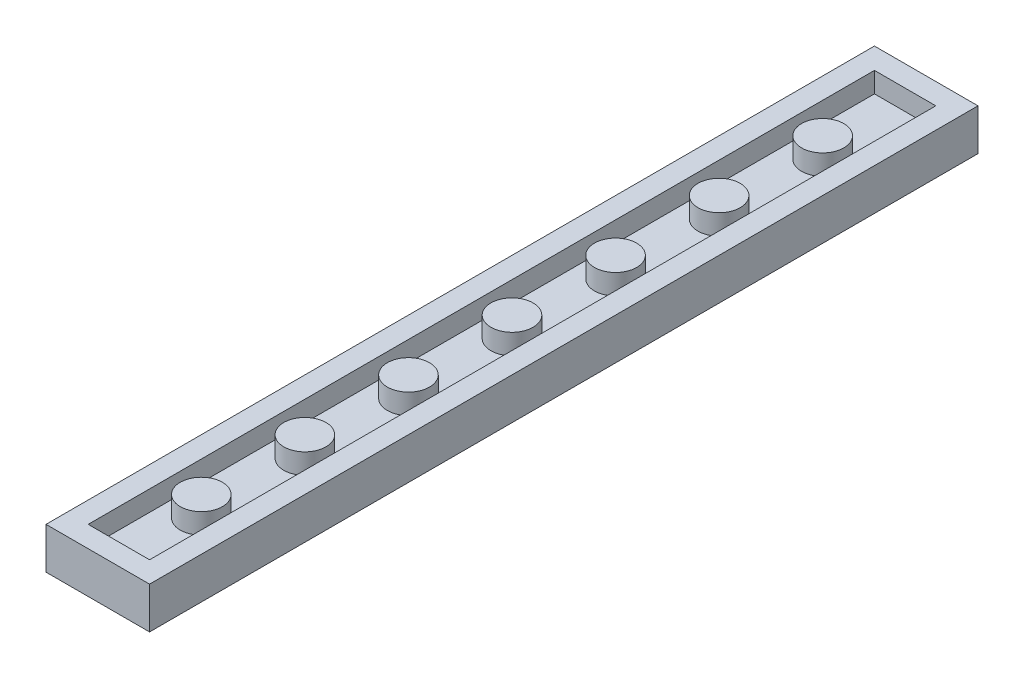
SolidWorks part; units mm, degrees
ref_plane "Front Plane" through (0, 0, 0) normal (0, 0, 1) x (1, 0, 0)
ref_plane "Top Plane" through (0, 0, 0) normal (0, 1, 0) x (1, 0, 0)
ref_plane "Right Plane" through (0, 0, 0) normal (1, 0, 0) x (0, 0, -1)
ref_plane "Plane1" through (0, 3.226, 0) normal (0, 1, 0) x (1, 0, 0)
sketch "Sketch1" plane through (0, 3.226, 0) normal (0, 1, 0) x (1, 0, 0)
  line L0 (4.0325, -16.13) -> (4.0325, 48.39)
  line L1 (4.0325, 48.39) -> (-4.0325, 48.39)
  line L2 (-4.0325, 48.39) -> (-4.0325, -16.13)
  line L3 (-4.0325, -16.13) -> (4.0325, -16.13)
  dimension "D1" = 64.52
extrude "Boss-Extrude1" add sketch "Sketch1" against normal blind 3.226
sketch "Sketch2" plane through (0, 3.226, 0) normal (0, 1, 0) x (-1, 0, 0)
  line L0 (2.39, 14.4875) -> (-2.39, 14.4875)
  line L1 (-2.39, 14.4875) -> (-2.39, -14.4875)
  line L3 (2.39, -14.4875) -> (2.39, 14.4875)
  line L6 (2.39, -46.7475) -> (-2.39, -46.7475)
  line L7 (-2.39, -46.7475) -> (-2.39, -14.4875)
  line L8 (2.39, -14.4875) -> (2.39, -46.7475)
extrude "Cut-Extrude1" cut sketch "Sketch2" against normal blind 1.5835
ref_plane "Plane2" through (0, 0, 12.0975) normal (0, 0, -1) x (-1, 0, 0)
ref_plane "Plane3" through (0, 0, 4.0325) normal (0, 0, -1) x (-1, 0, 0)
ref_plane "Plane4" through (0, 0, -4.0325) normal (0, 0, -1) x (-1, 0, 0)
ref_plane "Plane5" through (0, 0, -12.0975) normal (0, 0, -1) x (-1, 0, 0)
ref_plane "Plane6" through (0, 0, -8.065) normal (0, 0, -1) x (-1, 0, 0)
sketch "Sketch7" plane through (0, 0, -8.065) normal (0, 0, -1) x (-1, 0, 0)
  line L0 (-1.6425, 1.6425) -> (0, 1.6425)
  line L1 (0, 1.6425) -> (0, 3.226)
  line L2 (0, 3.226) -> (-1.6425, 3.226)
  line L3 (-1.6425, 3.226) -> (-1.6425, 1.6425)
  line L4 (0, 1.6425) -> (0, 3.226) construction
revolve "Revolve5" add sketch "Sketch7" angle 360 about L4
ref_plane "Plane7" through (0, 0, 0) normal (0, 0, -1) x (-1, 0, 0)
sketch "Sketch8" plane through (0, 0, 0) normal (0, 0, -1) x (-1, 0, 0)
  line L0 (-1.6425, 1.6425) -> (0, 1.6425)
  line L1 (0, 1.6425) -> (0, 3.226)
  line L2 (0, 3.226) -> (-1.6425, 3.226)
  line L3 (-1.6425, 3.226) -> (-1.6425, 1.6425)
  line L4 (0, 1.6425) -> (0, 3.226) construction
revolve "Revolve6" add sketch "Sketch8" angle 360 about L4
ref_plane "Plane8" through (0, 0, 8.065) normal (0, 0, -1) x (-1, 0, 0)
sketch "Sketch9" plane through (0, 0, 8.065) normal (0, 0, -1) x (-1, 0, 0)
  line L0 (-1.6425, 1.6425) -> (0, 1.6425)
  line L1 (0, 1.6425) -> (0, 3.226)
  line L2 (0, 3.226) -> (-1.6425, 3.226)
  line L3 (-1.6425, 3.226) -> (-1.6425, 1.6425)
  line L4 (0, 1.6425) -> (0, 3.226) construction
revolve "Revolve7" add sketch "Sketch9" angle 360 about L4
sketch "Sketch10" plane through (0, 3.226, 0) normal (0, 1, 0) x (1, 0, 0)
  line L0 (-4.0325, 16.13) -> (8.1472, 16.13)
  line L1 (-4.0325, 48.39) -> (-4.0325, -16.13) construction
pattern_linear "LPattern1" count 5 spacing 8.065 along (0, 0, -1) of "Revolve5"
